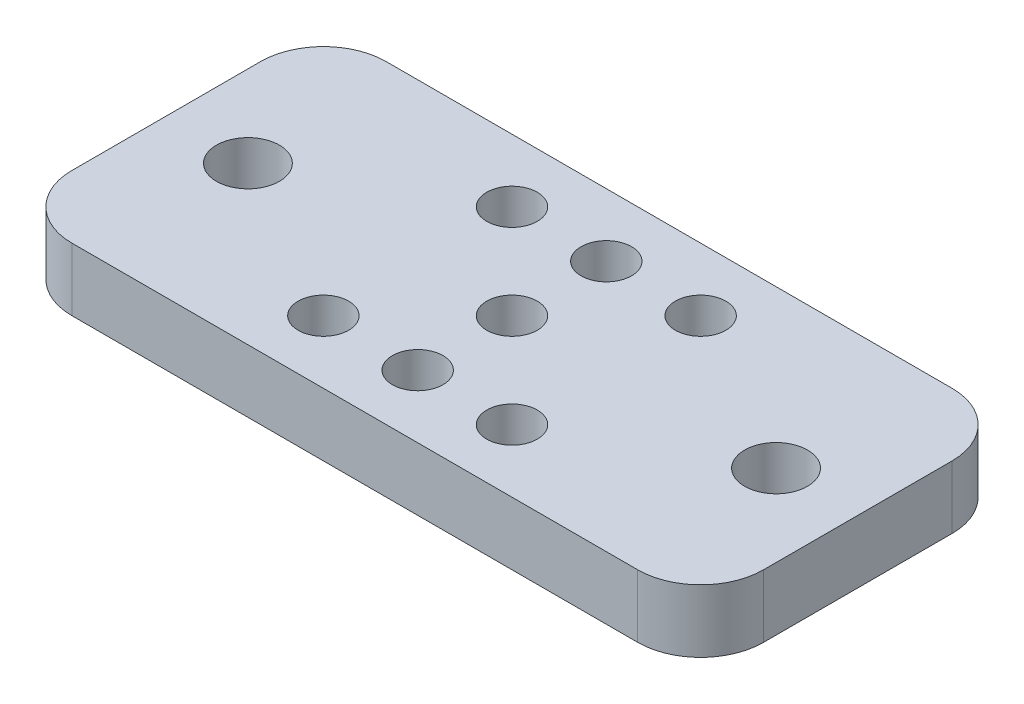
SolidWorks part; units mm, degrees
ref_plane "Front Plane" through (0, 0, 0) normal (0, 0, 1) x (1, 0, 0)
ref_plane "Top Plane" through (0, 0, 0) normal (0, 1, 0) x (1, 0, 0)
ref_plane "Right Plane" through (0, 0, 0) normal (1, 0, 0) x (0, 0, -1)
ref_plane "Plane1" through (0, 0, 0) normal (0, -1, 0) x (1, 0, 0)
sketch "Sketch1" plane through (0, 0, 0) normal (0, -1, 0) x (1, 0, 0)
  line L0 (34.925, -15.875) -> (34.925, 15.875)
  line L1 (34.925, 15.875) -> (-34.925, 15.875)
  line L2 (-34.925, 15.875) -> (-34.925, -15.875)
  line L3 (-34.925, -15.875) -> (34.925, -15.875)
extrude "Boss-Extrude1" add sketch "Sketch1" against normal blind 6.35
hole_wizard "Hole1" positions "Sketch3" profile "Sketch2" legacy
sketch "Sketch3" plane through (0, 6.35, 0) normal (0, 1, 0) x (1, 0, 0)
  point P0 (26.67, 0)
  point P1 (-26.67, 0)
sketch "Sketch2" plane through (26.67, 6.35, 0) normal (1, 0, 0) x (0, 0, 1)
  line L0 (0, 0) -> (0, 6.35)
  line L1 (0, 6.35) -> (3.175, 6.35)
  line L2 (3.175, 6.35) -> (3.175, 0)
  line L3 (3.175, 0) -> (0, 0)
  line L4 (0, 110) -> (0, -10) construction
  dimension "Diameter" = 6.35
  dimension "Depth" = 6.35
hole_wizard "Hole2" positions "Sketch5" profile "Sketch4" legacy
sketch "Sketch5" plane through (0, 0, 0) normal (0, -1, 0) x (-1, 0, 0)
  point P0 (0, 0)
  point P1 (0, 9.525)
  point P2 (0, -9.525)
  point P3 (9.525, 9.525)
  point P4 (-9.525, 9.525)
  point P5 (-9.525, -9.525)
  point P6 (9.525, -9.525)
sketch "Sketch4" plane through (0, 0, 0) normal (1, 0, 0) x (0, 0, -1)
  line L0 (0, 0) -> (0, 6.35)
  line L1 (0, 6.35) -> (2.5527, 6.35)
  line L2 (2.5527, 6.35) -> (2.5527, 1.9608)
  line L3 (2.5527, 1.9608) -> (4.8895, 0)
  line L4 (4.8895, 0) -> (0, 0)
  line L5 (0, -6.4453) -> (0, 115.525) construction
  line L6 (-2.5527, 1.9608) -> (-4.8895, 0) construction
  dimension "Diameter" = 5.1054
  dimension "Depth" = 6.35
  dimension "C-Sink Angle" = 100
  dimension "C-Sink Diameter" = 9.779
fillet "Fillet1" radius 6.35 4 edges at (34.925, 3.175, -15.875) (-34.925, 3.175, -15.875) (34.925, 3.175, 15.875) (-34.925, 3.175, 15.875)
